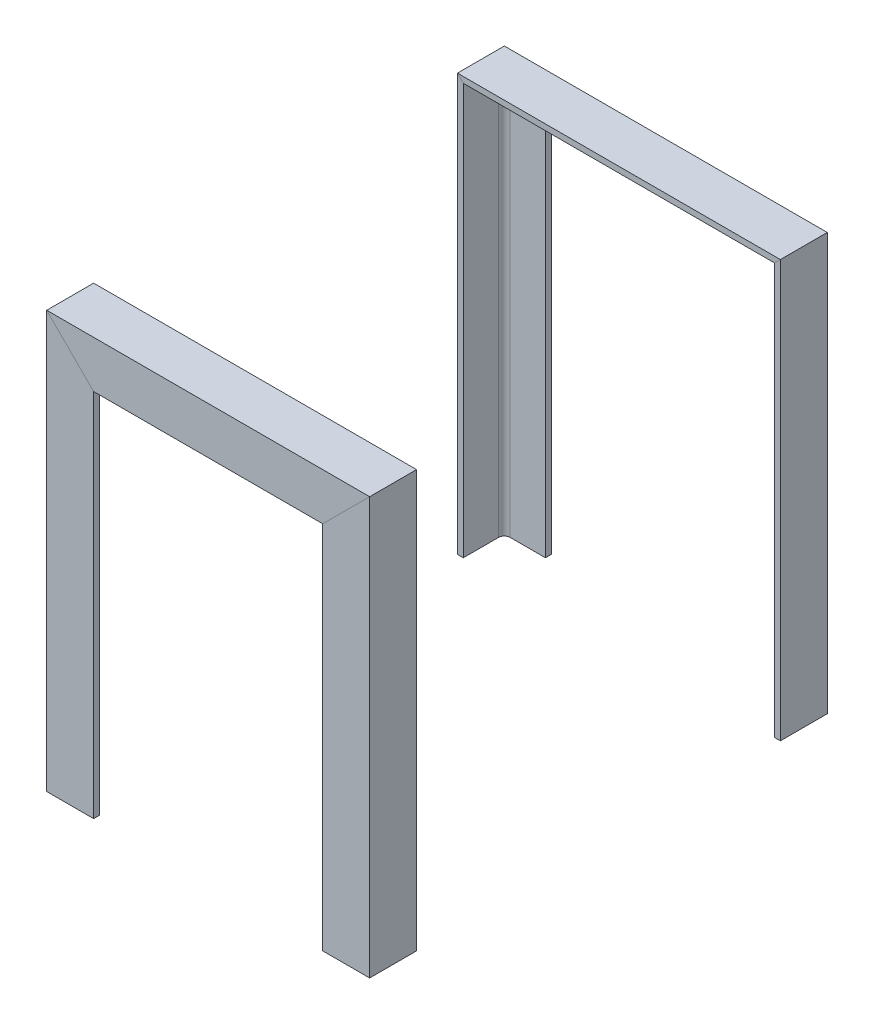
SolidWorks part; units mm, degrees
ref_plane "Alzado" through (0, 0, 0) normal (0, 0, 1) x (1, 0, 0)
ref_plane "Planta" through (0, 0, 0) normal (0, 1, 0) x (1, 0, 0)
ref_plane "Vista lateral" through (0, 0, 0) normal (1, 0, 0) x (0, 0, -1)
sketch3d "Croquis3D1"
  line L0 (0, 0, 0) -> (0, 225.552, 0)
  line L1 (0, 225.552, 0) -> (174.752, 225.552, 0)
  line L2 (174.752, 225.552, 0) -> (174.752, 0, 0)
  line L3 (174.752, 0, 0) -> (0, 0, 0) construction
  line L4 (174.752, 225.552, 0) -> (174.752, 225.552, 247.65)
  line L5 (0, 225.552, 0) -> (0, 225.552, 247.65)
  line L6 (0, 225.552, 247.65) -> (174.752, 225.552, 247.65)
  line L7 (174.752, 225.552, 247.65) -> (174.752, 0, 247.65)
  line L9 (0, 225.552, 247.65) -> (0, 0, 247.65)
  dimension "D1" = 225.552
  dimension "D2" = 174.752
  dimension "D3" = 247.65
other "Ángulo de extremos cuadrados al ls AL LS ANGLE SQR END 1 X 1 X 0.125(1)"
ref_plane "Plano2" through (0, 0, 0) normal (0, -1, 0) x (1, 0, 0)
sketch "Sketch1" plane through (0, 0, 0) normal (0, -1, 0) x (1, 0, 0)
  line L0 (0, 0) -> (0, 25.4)
  line L2 (3.175, 25.4) -> (3.175, 6.35)
  line L3 (6.35, 3.175) -> (25.4, 3.175)
  line L5 (25.4, 0) -> (0, 0)
  line L6 (0, 25.4) -> (3.175, 25.4)
  line L7 (25.4, 0) -> (25.4, 3.175)
  arc A2 (6.35, 3.175) -> (3.175, 6.35) centre (6.35, 6.35) cw
  point P1 (0, 0)
  point P10 (0, 12.7)
  point P11 (12.7, 0)
  dimension "Radius_1" = 3.175
  dimension "V_leg" = 25.4
  dimension "H_leg" = 25.4
  dimension "Thickness" = 3.175
other "Ángulo de extremos cuadrados al ls AL LS ANGLE SQR END 1 X 1 X 0.125(4)"
ref_plane "Plano4" through (174.752, 225.552, 247.65) normal (0, 1, 0) x (0, 0, -1)
sketch "Sketch12" plane through (174.752, 225.552, 247.65) normal (0, 1, 0) x (0, 0, -1)
  line L0 (0, 0) -> (0, 25.4)
  line L2 (3.175, 25.4) -> (3.175, 6.35)
  line L3 (6.35, 3.175) -> (25.4, 3.175)
  line L5 (25.4, 0) -> (0, 0)
  line L6 (0, 25.4) -> (3.175, 25.4)
  line L7 (25.4, 0) -> (25.4, 3.175)
  arc A2 (6.35, 3.175) -> (3.175, 6.35) centre (6.35, 6.35) cw
  point P1 (0, 0)
  point P10 (0, 12.7)
  point P11 (12.7, 0)
  dimension "Radius_1" = 3.175
  dimension "V_leg" = 25.4
  dimension "H_leg" = 25.4
  dimension "Thickness" = 3.175
